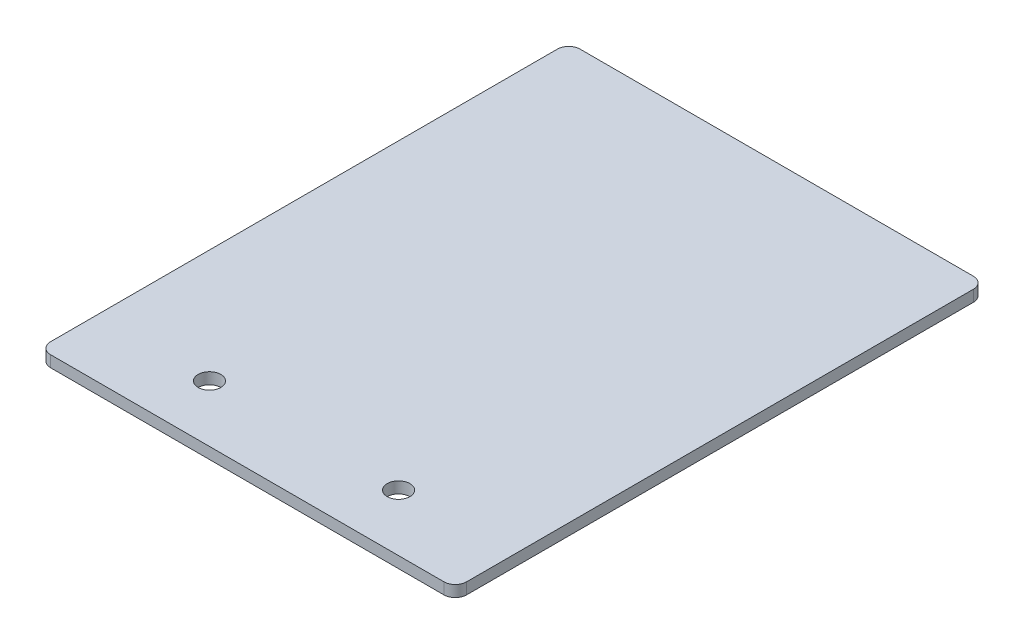
SolidWorks part; units mm, degrees
ref_plane "前视基准面" through (0, 0, 0) normal (0, 0, 1) x (1, 0, 0)
ref_plane "上视基准面" through (0, 0, 0) normal (0, 1, 0) x (1, 0, 0)
ref_plane "右视基准面" through (0, 0, 0) normal (1, 0, 0) x (0, 0, -1)
sketch "草图1" plane through (0, 0, 0) normal (0, 1, 0) x (1, 0, 0)
  line L1 (-55, 70) -> (55, 70)
  line L2 (-55, 70) -> (-55, -70)
  line L3 (-55, -70) -> (55, -70)
  line L4 (55, 70) -> (55, -70)
  line L5 (-55, 70) -> (55, -70) construction
  line L6 (-55, -70) -> (55, 70) construction
  point P0 (0, 0)
  dimension "D1" = 140
  dimension "D2" = 110
extrude "凸台-拉伸1" add sketch "草图1" along normal blind 3
sketch "草图2" plane through (0, 0, 0) normal (0, -1, 0) x (1, 0, 0)
  line L0 (55, -70) -> (-55, -70) construction
  line L1 (0, 75.896) -> (0, -87.7185) construction
  circle A0 centre (-25, 55) radius 3
  circle A1 centre (25, 55) radius 3
  dimension "D3" = 6
  dimension "D1" = 125
  dimension "D2" = 50
extrude "切除-拉伸1" cut sketch "草图2" against normal blind 3
fillet "圆角1" radius 3 4 edges at (-55, 1.5, -70) (55, 1.5, -70) (55, 1.5, 70) (-55, 1.5, 70)
